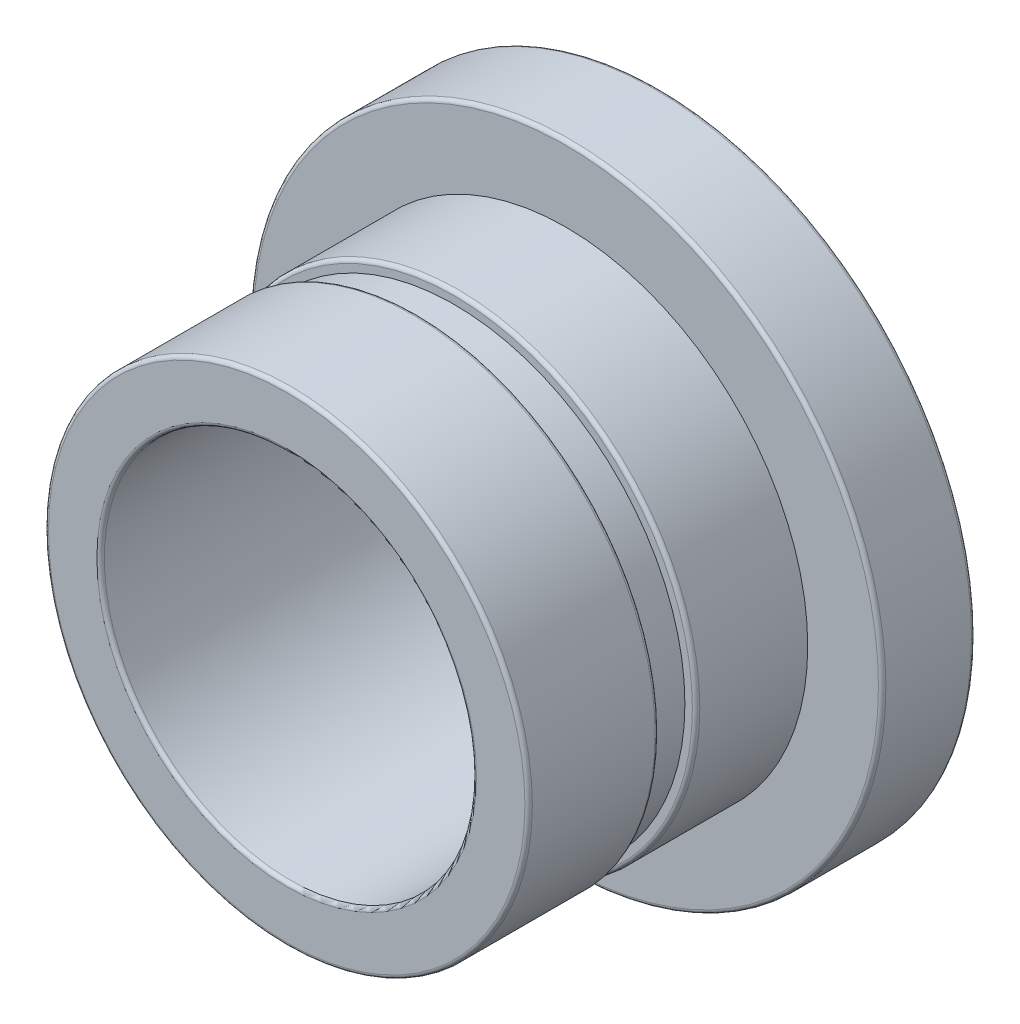
SolidWorks part; units mm, degrees
material "Manganese Bronze"
ref_plane "Front Plane" through (0, 0, 0) normal (0, 0, 1) x (1, 0, 0)
ref_plane "Top Plane" through (0, 0, 0) normal (0, 1, 0) x (1, 0, 0)
ref_plane "Right Plane" through (0, 0, 0) normal (1, 0, 0) x (0, 0, -1)
sketch "Sketch1" plane through (0, 0, 0) normal (0, 0, 1) x (1, 0, 0)
  circle A0 centre (0, 0) radius 8.5
  dimension "D1" = 17
extrude "Extrude1" add sketch "Sketch1" along normal blind 2.5
sketch "Sketch2" plane through (0, 0, 2.5) normal (0, 0, 1) x (1, 0, 0)
  circle A0 centre (0, 0) radius 6.5
  dimension "D1" = 13
extrude "Extrude2" add sketch "Sketch2" along normal blind 7.5
sketch "Sketch3" plane through (0, 0, 10) normal (0, 0, 1) x (1, 0, 0)
  circle A0 centre (0, 0) radius 5
  dimension "D1" = 10
extrude "Cut-Extrude1" cut sketch "Sketch3" against normal through all
fillet "Fillet1" radius 0.1 5 edges at (5, 0, 0) (5, 0, 10) (8.5, 0, 0) (8.5, 0, 2.5) (6.5, 0, 10)
sketch "Sketch4" plane through (0, 0, 10) normal (0, 0, 1) x (1, 0, 0)
  circle A0 centre (0, 0) radius 6.2
  circle A1 centre (0, 0) radius 6.5
  circle A2 centre (0, 0) radius 6.5 construction
  dimension "D1" = 12.4
extrude "Cut-Extrude2" cut sketch "Sketch4" against normal blind 1 from offset 3.5
fillet "Fillet2" radius 0.1 2 edges at (6.5, 0, 5.5) (6.5, 0, 6.5)
